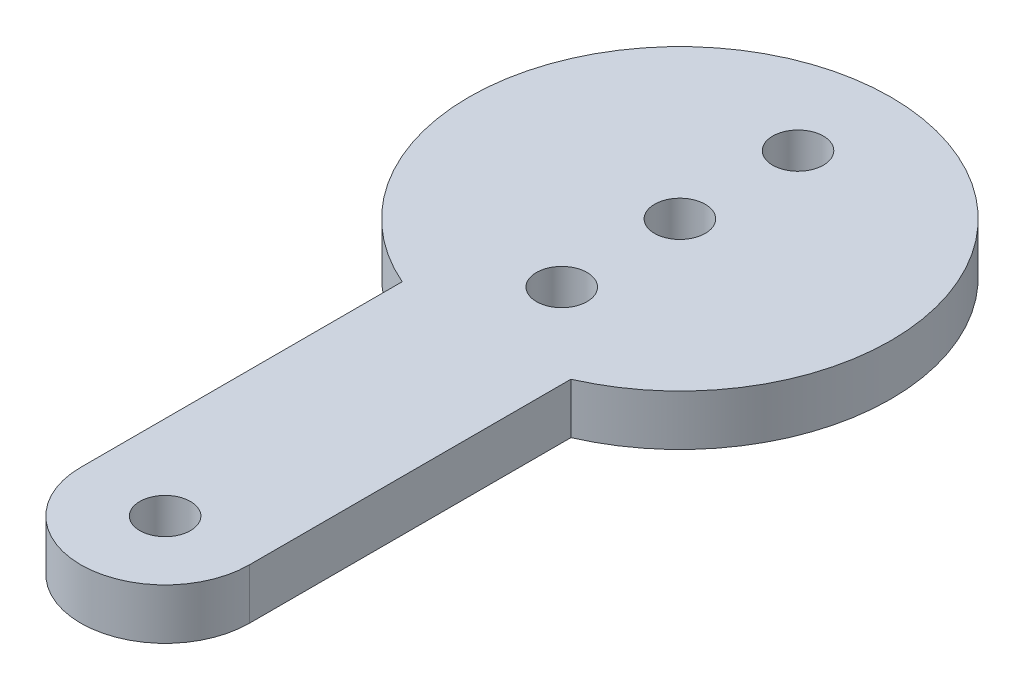
SolidWorks part; units mm, degrees
ref_plane "Front Plane" through (0, 0, 0) normal (0, 0, 1) x (1, 0, 0)
ref_plane "Top Plane" through (0, 0, 0) normal (0, 1, 0) x (1, 0, 0)
ref_plane "Right Plane" through (0, 0, 0) normal (1, 0, 0) x (0, 0, -1)
sketch "Sketch1" plane through (0, 0, 0) normal (0, 1, 0) x (1, 0, 0)
  line L0 (0, 0) -> (0, -30.5) construction
  line L1 (5, 0) -> (5, -30.5) construction
  line L2 (-5, 0) -> (-5, -30.5) construction
  line L3 (-5, -11.4564) -> (-5, -30.5)
  line L4 (-5, -30.5) -> (5, -30.5) construction
  line L5 (5, -30.5) -> (5, -11.4564)
  line L6 (0, 0) -> (0, 7) construction
  arc A0 (5, 0) -> (-5, 0) centre (0, 0) ccw construction
  arc A1 (-5, -30.5) -> (5, -30.5) centre (0, -30.5) ccw construction
  circle A2 centre (0, 0) radius 12.5 construction
  arc A3 (-5, -11.4564) -> (5, -11.4564) centre (0, 0) cw
  arc A4 (-5, -30.5) -> (5, -30.5) centre (0, -30.5) ccw
  circle A5 centre (0, 0) radius 1.5
  circle A6 centre (0, 7) radius 1.5
  circle A7 centre (0, -7) radius 1.5
  circle A8 centre (0, -30.5) radius 1.5
  point P3 (0, -15.25)
  dimension "D1" = 5
  dimension "D2" = 25
  dimension "D4" = 7
  dimension "D6" = 3
  dimension "D7" = 3
  dimension "D8" = 3
  dimension "D3" = 30.5
  dimension "D5" = 7
extrude "Boss-Extrude1" add sketch "Sketch1" along normal blind 3 contours L3 A4 L5 A3 A7 A6 A5
